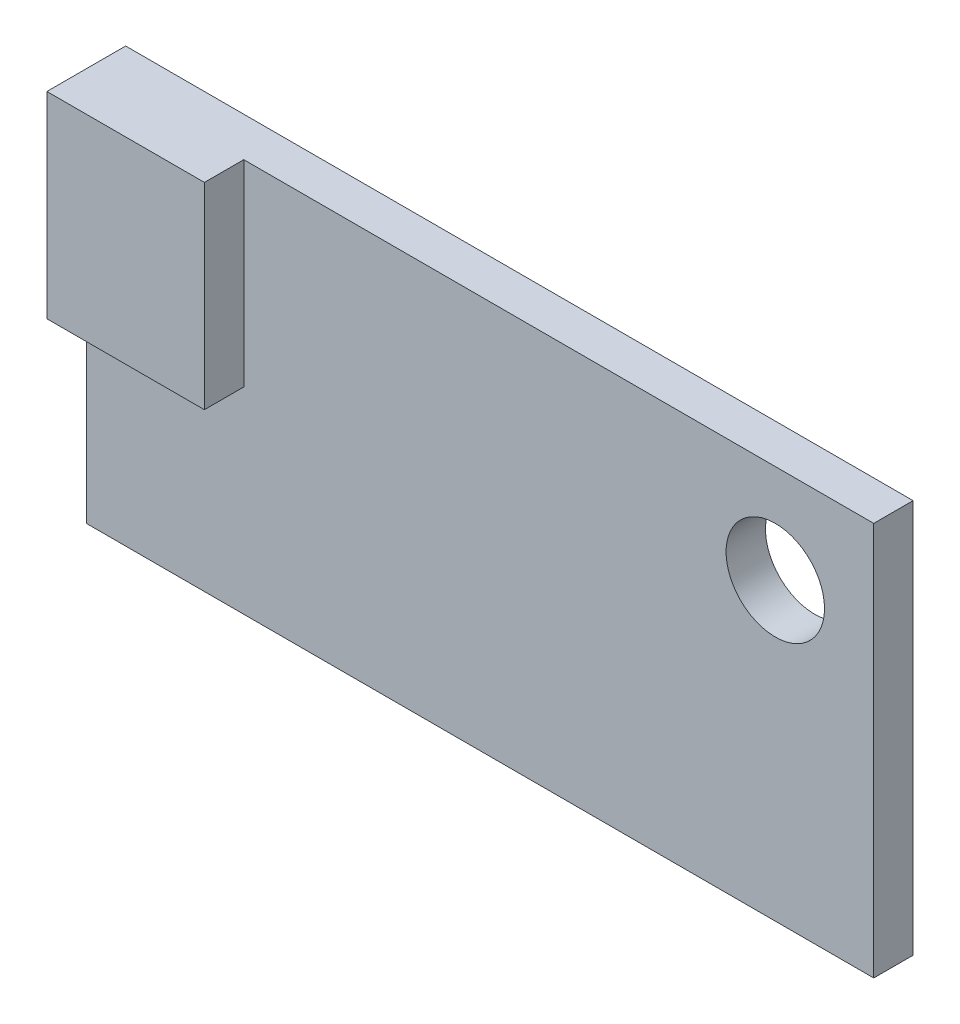
SolidWorks part; units mm, degrees
ref_plane "Alzado" through (0, 0, 0) normal (0, 0, 1) x (1, 0, 0)
ref_plane "Planta" through (0, 0, 0) normal (0, 1, 0) x (1, 0, 0)
ref_plane "Vista lateral" through (0, 0, 0) normal (1, 0, 0) x (0, 0, -1)
sketch "Croquis2" plane through (0, 0, 0) normal (0, 0, 1) x (1, 0, 0)
  line L0 (0, 0) -> (200, 0)
  line L1 (5.5, 0) -> (-5.5, 0) construction
  line L2 (200, 0) -> (200, 100)
  line L3 (0, 0) -> (0, 100)
  line L4 (0, 100) -> (200, 100)
  line L5 (200, 100) -> (175, 100)
  circle A0 centre (175, 75) radius 12.5
  dimension "D3" = 25
  dimension "D1" = 200
  dimension "D2" = 100
  dimension "D4" = 25
  dimension "D5" = 25
extrude "Saliente-Extruir5" add sketch "Croquis2" along normal blind 10 contours L4 L3 L0 L2 A0
sketch "Croquis11" plane through (0, 0, 10) normal (0, 0, 1) x (1, 0, 0)
  line L0 (0, 100) -> (200, 100) construction
  line L1 (40, 100) -> (0, 100)
  line L2 (40, 100) -> (40, 50)
  line L3 (40, 50) -> (0, 50)
  line L4 (0, 100) -> (0, 50)
  line L5 (0, -5.5) -> (0, 5.5) construction
  dimension "D1" = 40
  dimension "D2" = 50
extrude "Saliente-Extruir6" add sketch "Croquis11" along normal blind 10
ref_plane "Plano1" through (40, 100, 20) normal (-1, 0, 0) x (0, 0, 1)
